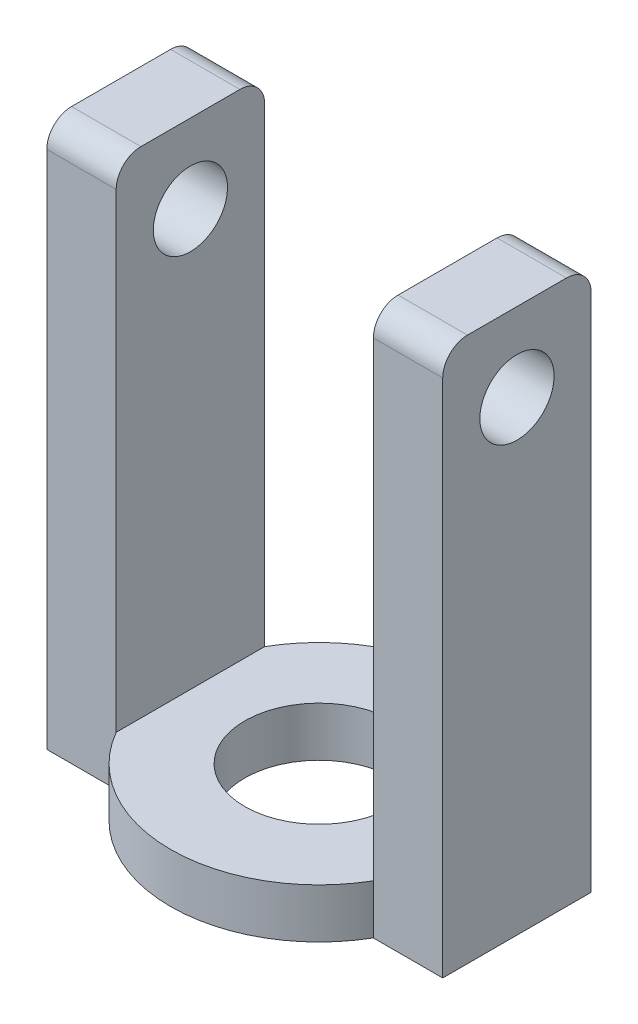
SolidWorks part; units mm, degrees
ref_plane "Front Plane" through (0, 0, 0) normal (0, 0, 1) x (1, 0, 0)
ref_plane "Top Plane" through (0, 0, 0) normal (0, 1, 0) x (1, 0, 0)
ref_plane "Right Plane" through (0, 0, 0) normal (1, 0, 0) x (0, 0, -1)
sketch "Sketch1" plane through (0, 0, 0) normal (0, 1, 0) x (1, 0, 0)
  line L1 (-400, 150) -> (400, 150)
  line L2 (-400, 150) -> (-400, -150)
  line L3 (-400, -150) -> (400, -150)
  line L4 (400, 150) -> (400, -150)
  circle A0 centre (0, 0) radius 300
  dimension "D1" = 400
  dimension "D5" = 600
  dimension "D2" = 400
  dimension "D3" = 150
  dimension "D4" = 150
extrude "Boss-Extrude1" add sketch "Sketch1" along normal blind 100 contours L1 A0 | L3 A0 L1 | L3 A0 | A0 L1 L2 L3 | A0 L3 L4 L1
sketch "Sketch2" plane through (0, 100, 0) normal (0, 1, 0) x (1, 0, 0)
  line L1 (-400, 150) -> (-259.8076, 150)
  line L2 (-400, 150) -> (-400, -150)
  line L3 (-400, -150) -> (-259.8076, -150)
  line L4 (-259.8076, 150) -> (-259.8076, -150)
  line L5 (259.8076, 150) -> (400, 150)
  line L6 (259.8076, 150) -> (259.8076, -150)
  line L7 (259.8076, -150) -> (400, -150)
  line L8 (400, 150) -> (400, -150)
extrude "Boss-Extrude2" add sketch "Sketch2" along normal blind 1000 contours L2 L1 L4 L3 | L6 L5 L8 L7
sketch "Sketch3" plane through (0, 100, 0) normal (0, 1, 0) x (1, 0, 0)
  circle A0 centre (0, 0) radius 150
extrude "Cut-Extrude1" cut sketch "Sketch3" against normal blind 100
fillet "Fillet1" radius 50 4 edges at (-329.9038, 1100, 150) (-329.9038, 1100, -150) (329.9038, 1100, 150) (329.9038, 1100, -150)
sketch "Sketch4" plane through (-400, 0, 0) normal (-1, 0, 0) x (0, 0, 1)
  circle A0 centre (0, 941.0645) radius 75
extrude "Cut-Extrude2" cut sketch "Sketch4" against normal up to vertex
